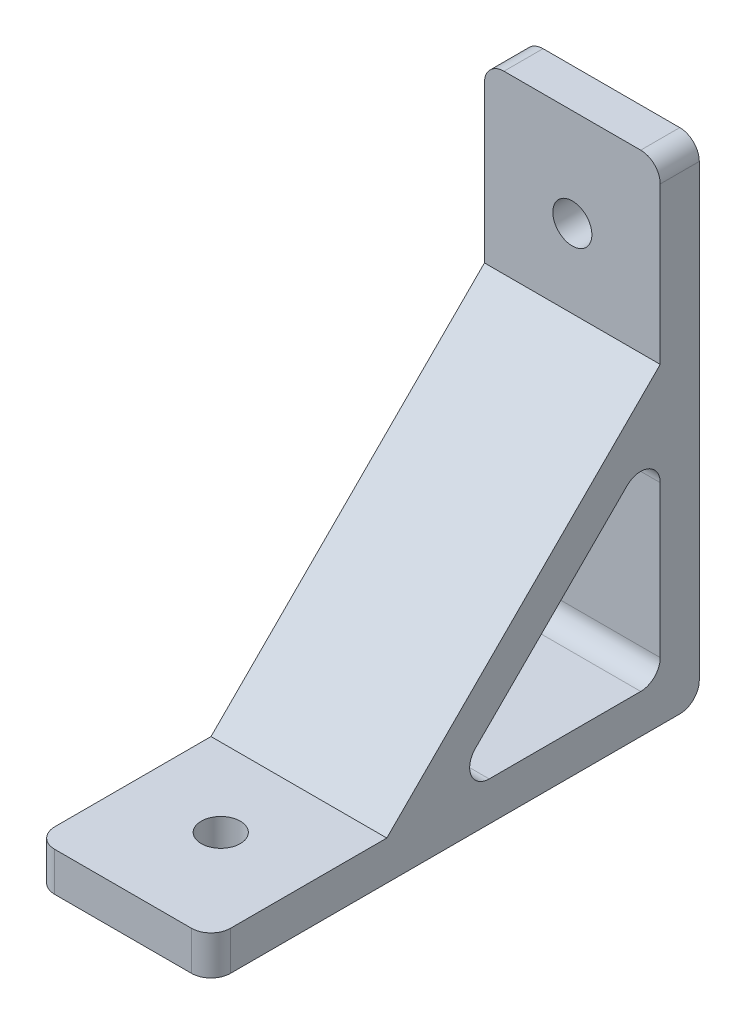
SolidWorks part; units mm, degrees
material "Alloy Steel"
ref_plane "Front Plane" through (0, 0, 0) normal (0, 0, 1) x (1, 0, 0)
ref_plane "Top Plane" through (0, 0, 0) normal (0, 1, 0) x (1, 0, 0)
ref_plane "Right Plane" through (0, 0, 0) normal (1, 0, 0) x (0, 0, -1)
sketch "Sketch1" plane through (0, 0, 0) normal (0, 1, 0) x (1, 0, 0)
  line L1 (-18, 50) -> (18, 50)
  line L2 (-18, 50) -> (-18, -50)
  line L3 (-18, -50) -> (18, -50)
  line L4 (18, 50) -> (18, -50)
  line L5 (-18, 50) -> (18, -50) construction
  line L6 (-18, -50) -> (18, 50) construction
  point P0 (0, 0)
  dimension "D1" = 36
  dimension "D2" = 100
extrude "Boss-Extrude1" add sketch "Sketch1" along normal blind 100
sketch "Sketch2" plane through (-18, 0, 0) normal (-1, 0, 0) x (0, 0, 1)
  line L0 (-50, 100) -> (-78, 100)
  line L1 (-50, 100) -> (50, 100) construction
  line L2 (-78, 100) -> (50, -28)
  line L3 (50, 100) -> (50, 0) construction
  line L4 (50, -28) -> (50, 0)
  line L5 (50, -28) -> (50, 100)
  line L6 (50, 100) -> (-78, 100)
  line L7 (50, -28) -> (50, 8)
  line L8 (-50, 0) -> (50, 0) construction
  line L9 (-47.5, 0) -> (-50, 2.5)
  line L10 (-50, 100) -> (-50, 0) construction
  line L11 (50, 8) -> (14, 8)
  line L12 (-78, 100) -> (-42, 100)
  line L13 (-42, 100) -> (-42, 64)
  line M4 (50, 0) -> (50, 100)
  line M5 (50, 100) -> (-50, 100)
  dimension "D1" = 8
  dimension "D2" = 8
  dimension "D3" = 2.5
  dimension "D4" = 2.5
  dimension "D5" = 36
  dimension "D6" = 36
  dimension "D7" = 181.0193
extrude "Cut-Extrude1" cut sketch "Sketch2" against normal through all both and the other way through all contours L2 M5 M4
sketch "Sketch8" plane through (18, 0, 0) normal (1, 0, 0) x (0, 0, -1)
  line L0 (42, 43.0294) -> (42, 12)
  line L1 (38, 8) -> (6.9706, 8)
  line L2 (4.1421, 14.8284) -> (35.1716, 45.8579)
  line L4 (42, 64) -> (-14, 8) construction
  line L5 (42, 100) -> (42, 64) construction
  line L6 (-50, 8) -> (-14, 8) construction
  arc A0 (6.9706, 8) -> (4.1421, 14.8284) centre (6.9706, 12) cw
  arc A1 (38, 8) -> (42, 12) centre (38, 12) ccw
  arc A2 (42, 43.0294) -> (35.1716, 45.8579) centre (38, 43.0294) ccw
  dimension "D2" = 4
  dimension "D1" = 8
extrude "Cut-Extrude5" cut sketch "Sketch8" against normal through all both and the other way through all
fillet "Fillet3" radius 4 5 edges at (0, 0, -50) (-18, 4, 50) (18, 4, 50) (18, 100, -46) (-18, 100, -46)
sketch "Sketch9" plane through (0, 8, 0) normal (0, 1, 0) x (1, 0, 0)
  line L0 (18, -46) -> (18, -14) construction
  line L1 (18, -14) -> (-18, -14) construction
  circle A0 centre (0, -30) radius 4
  point P2 (18, -30)
  point P8 (0, -14)
  dimension "D1" = 8
extrude "Cut-Extrude6" cut sketch "Sketch9" against normal through all both and the other way through all
sketch "Sketch10" plane through (0, 0, -42) normal (0, 0, 1) x (1, 0, 0)
  line L2 (18, 96) -> (18, 64) construction
  line L3 (14, 100) -> (-14, 100) construction
  circle A0 centre (0, 80) radius 4
  point P2 (18, 80)
  point P8 (0, 100)
  dimension "D1" = 8
extrude "Cut-Extrude7" cut sketch "Sketch10" against normal through all both and the other way through all contours A0
